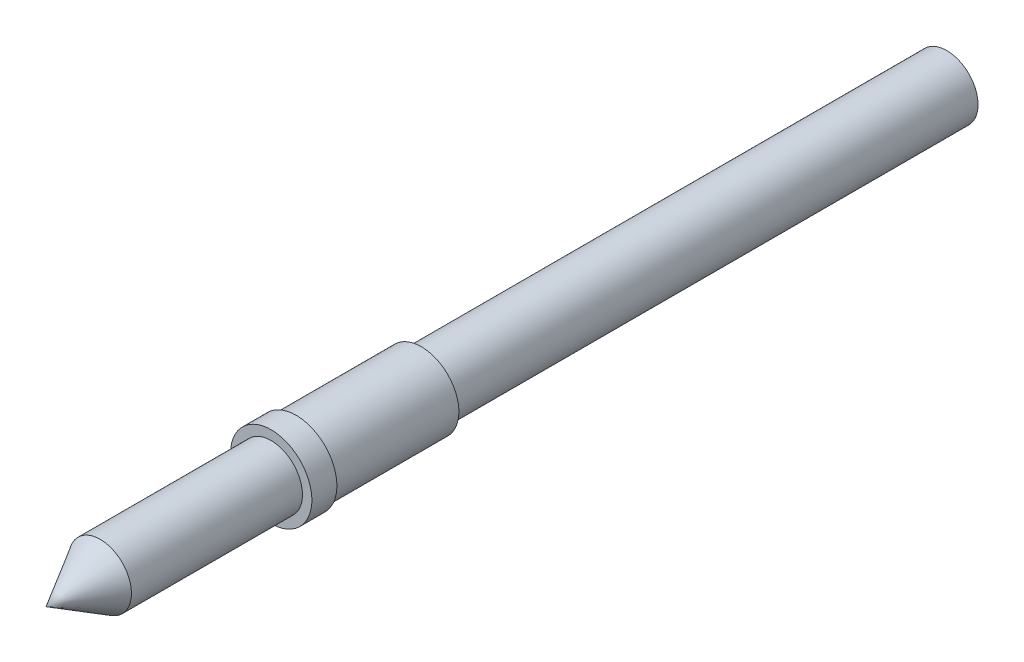
SolidWorks part; units mm, degrees
ref_plane "Front Plane" through (0, 0, 0) normal (0, 0, 1) x (1, 0, 0)
ref_plane "Top Plane" through (0, 0, 0) normal (0, 1, 0) x (1, 0, 0)
ref_plane "Right Plane" through (0, 0, 0) normal (1, 0, 0) x (0, 0, -1)
sketch "Sketch3" plane through (0, 0, 0) normal (1, 0, 0) x (0, 0, -1)
  line L0 (0, 0) -> (-259.5858, 0) construction
  line L1 (-214.8518, 7.9375) -> (-228.6, 0)
  line L4 (-228.6, 0) -> (0, 0)
  line L6 (-214.8518, 7.9375) -> (-171.45, 7.9375)
  line L7 (-171.45, 7.9375) -> (-171.45, 10.3187)
  line L8 (-171.45, 10.3187) -> (-165.1, 10.3187)
  line L9 (-165.1, 10.3187) -> (-165.1, 9.525)
  line L10 (-165.1, 9.525) -> (-133.35, 9.525)
  line L11 (-133.35, 9.525) -> (-133.35, 7.9375)
  line L12 (-133.35, 7.9375) -> (0, 7.9375)
  line L13 (0, 7.9375) -> (0, 0)
  dimension "D1" = 30
  dimension "D2" = 15.875
  dimension "D3" = 20.6375
  dimension "D4" = 19.05
  dimension "D5" = 15.875
  dimension "D6" = 228.6
  dimension "D7" = 31.75
  dimension "D8" = 6.35
  dimension "D9" = 57.15
revolve "Revolve2" add sketch "Sketch3" angle 360 about L0
